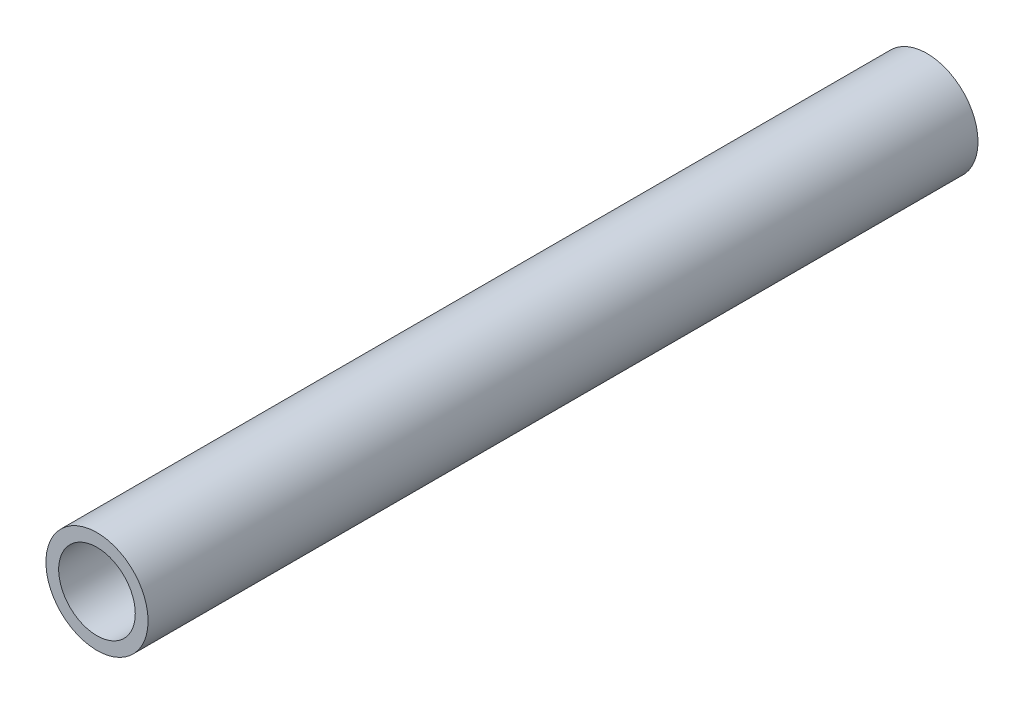
SolidWorks part; units mm, degrees
ref_plane "前视基准面" through (0, 0, 0) normal (0, 0, 1) x (1, 0, 0)
ref_plane "上视基准面" through (0, 0, 0) normal (0, 1, 0) x (1, 0, 0)
ref_plane "右视基准面" through (0, 0, 0) normal (1, 0, 0) x (0, 0, -1)
sketch "草图1" plane through (0, 0, 0) normal (0, 0, 1) x (1, 0, 0)
  circle A0 centre (0, 0) radius 8
  circle A1 centre (0, 0) radius 6
extrude "凸台-拉伸1" add sketch "草图1" along normal blind 130
